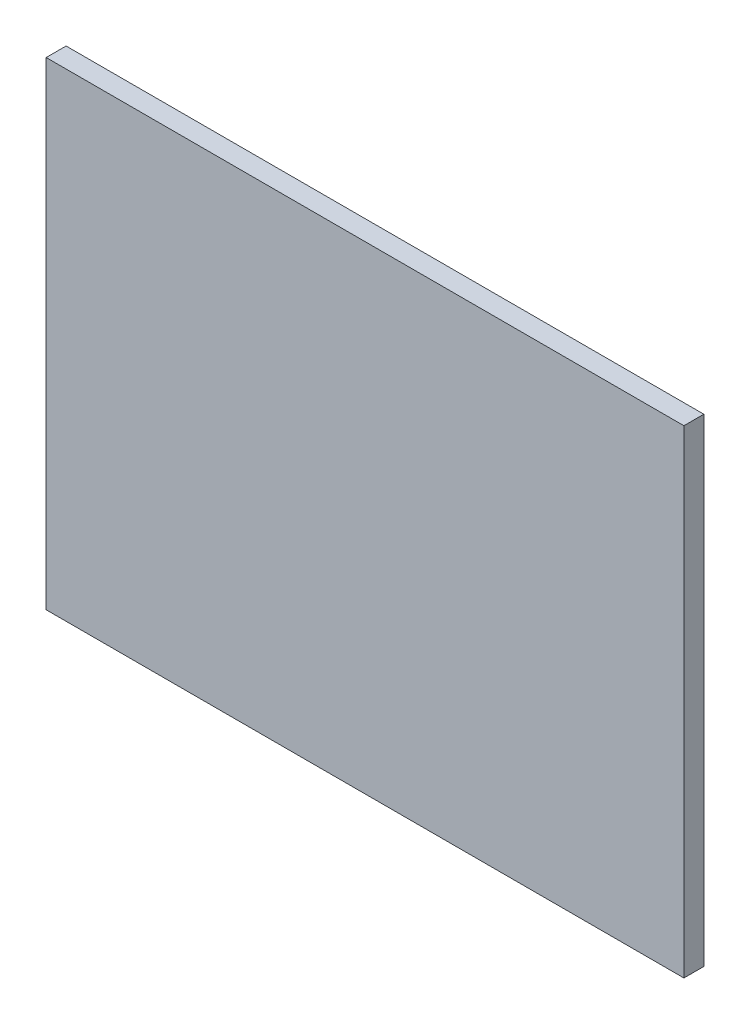
SolidWorks part; units mm, degrees
ref_plane "Front Plane" through (0, 0, 0) normal (0, 0, 1) x (1, 0, 0)
ref_plane "Top Plane" through (0, 0, 0) normal (0, 1, 0) x (1, 0, 0)
ref_plane "Right Plane" through (0, 0, 0) normal (1, 0, 0) x (0, 0, -1)
sketch "Sketch1" plane through (0, 0, 0) normal (0, 0, 1) x (1, 0, 0)
  line L1 (25.4, -19.05) -> (-25.4, -19.05)
  line L2 (25.4, -19.05) -> (25.4, 19.05)
  line L3 (25.4, 19.05) -> (-25.4, 19.05)
  line L4 (-25.4, -19.05) -> (-25.4, 19.05)
  line L5 (25.4, -19.05) -> (-25.4, 19.05) construction
  line L6 (25.4, 19.05) -> (-25.4, -19.05) construction
  point P0 (0, 0)
  dimension "D1" = 50.8
  dimension "D2" = 38.1
extrude "Boss-Extrude1" add sketch "Sketch1" along normal blind 1.5875
sketch "Sketch2" plane through (0, 0, 0) normal (0, 0, -1) x (-1, 0, 0)
  line L0 (-498.8385, 292.6423) -> (-98.8385, 292.6423) construction
  line L1 (74.3338, 252.7117) -> (473.0004, 252.7117) construction
